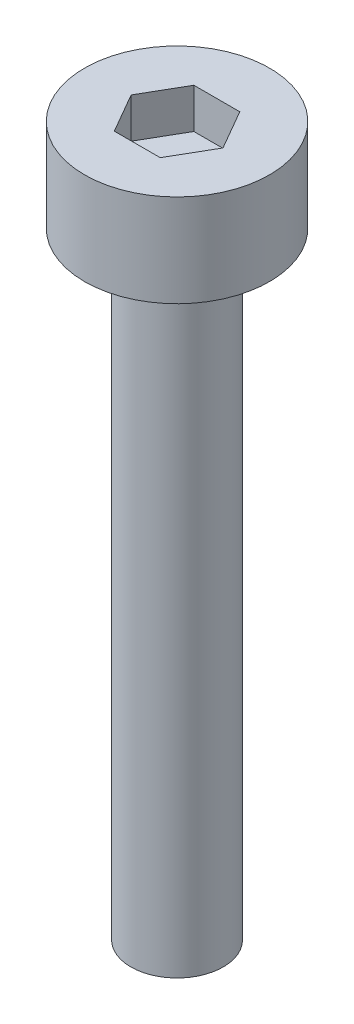
SolidWorks part; units mm, degrees
ref_plane "Front Plane" through (0, 0, 0) normal (0, 0, 1) x (1, 0, 0)
ref_plane "Top Plane" through (0, 0, 0) normal (0, 1, 0) x (1, 0, 0)
ref_plane "Right Plane" through (0, 0, 0) normal (1, 0, 0) x (0, 0, -1)
sketch "Sketch1" plane through (0, 0, 0) normal (0, 1, 0) x (1, 0, 0)
  circle A0 centre (0, 0) radius 1.5
  dimension "D1" = 3
extrude "ScrewShaft" add sketch "Sketch1" along normal blind 20
sketch "Sketch2" plane through (0, 20, 0) normal (0, 1, 0) x (1, 0, 0)
  circle A0 centre (0, 0) radius 3
  dimension "D1" = 6
extrude "Boss-Extrude2" add sketch "Sketch2" along normal blind 3
sketch "Sketch3" plane through (0, 23, 0) normal (0, 1, 0) x (1, 0, 0)
  line L0 (0, 0) -> (0, 1.29) construction
  line L1 (1.4896, 0) -> (0.7448, 1.29)
  line L2 (0.7448, 1.29) -> (-0.7448, 1.29)
  line L3 (-0.7448, 1.29) -> (-1.4896, 0)
  line L4 (-1.4896, 0) -> (-0.7448, -1.29)
  line L5 (-0.7448, -1.29) -> (0.7448, -1.29)
  line L6 (0.7448, -1.29) -> (1.4896, 0)
  circle A0 centre (0, 0) radius 1.29 construction
  dimension "D1" = 2.58
extrude "Cut-Extrude1" cut sketch "Sketch3" against normal blind 1.3
equation "\"X-ROD-SPACING\"=45"
equation "\"Y-ROD-SPACING\"=75"
equation "\"Z-ROD-SPACING\"=17.5"
equation "\"Y-BED-OFFSET\"=2"
equation "\"Y-BED-ROD-INSET\"=3.5"
equation "\"T-SLOT-NUT-FILLET-RADIUS\"=0.25"
equation "\"T-SLOT-SCREW-SHAFT-RADIUS\"=1.75"
equation "\"T-SLOT-SCREW-SHAFT-CUTOUT-LENGTH\"=10.5"
equation "\"T-SLOT-NUT-DEPTH\"=4.2"
equation "\"T-SLOT-NUT-WIDTH\"=3"
equation "\"T-SLOT-NUT-END-DISTANCE\"=8"
equation "\"ACRYLIC-THICKNESS\"=10"
equation "\"ACRYLIC-THICKNESS2\"=4.5"
equation "\"ACRYLIC-TAB-CUTOUT-SIZE\"=\"ACRYLIC-THICKNESS\"+\"ACRYLIC-TAB-TOLERANCE\"*2"
equation "\"ACRYLIC-TAB-WIDTH\"=\"ACRYLIC-THICKNESS\""
equation "\"ACRYLIC-M3-HOLE\"=3.2"
equation "\"SMOOTHROD-CAP-SCREW-DISTANCE\"=20"
equation "\"FRAME-WIDTH-INNER\"=370"
equation "\"NEMA17-HOLE-SPACING\"=31"
equation "\"NEMA17-CENTRAL-CUTOUT\"=22.5"
equation "\"Z-BRACKET-REACH\"=55"
equation "\"TOP-BRACKET-SPACING\"=40"
equation "\"SMOOTHROD-X-LENGTH\"=350"
equation "\"SMOOTHROD-Y-LENGTH\"=350"
equation "\"SMOOTHROD-Z-LENGTH\"=350"
equation "\"SMOOTHROD-TIGHTENING-HEADROOM\"=1"
equation "\"LEADSCREW-Z-LENGTH\"=300"
equation "\"SCREW-LENGTH-FRAME\"=\"ACRYLIC-THICKNESS\" + 10"
equation "\"SCREW-HEAD-RADIUS\"=6"
equation "\"PRINTED-X-SMOOTHROD-DIAMETER\"=8.2"
equation "\"PRINTED-X-SMOOTHROD-CUTOUT\"=10"
equation "\"PRINTED-X-BASE-HEIGHT\"=10"
equation "\"PRINTED-LM8UU-CUTOUT-SIZE\"=16"
equation "\"PRINTED-LM8UU-CUTOUT-LENGTH\"=24.5"
equation "\"PRINTED-X-IDLER-HEIGHT\"=16"
equation "\"PSU-MOUNTING-WIDTH\"=95"
equation "\"PSU-MOUNTING-HEIGHT\"=177"
equation "\"D1@ScrewShaft\"=\"SCREW-LENGTH-FRAME\""
equation "\"D1@Sketch2\"=\"SCREW-HEAD-RADIUS\""
